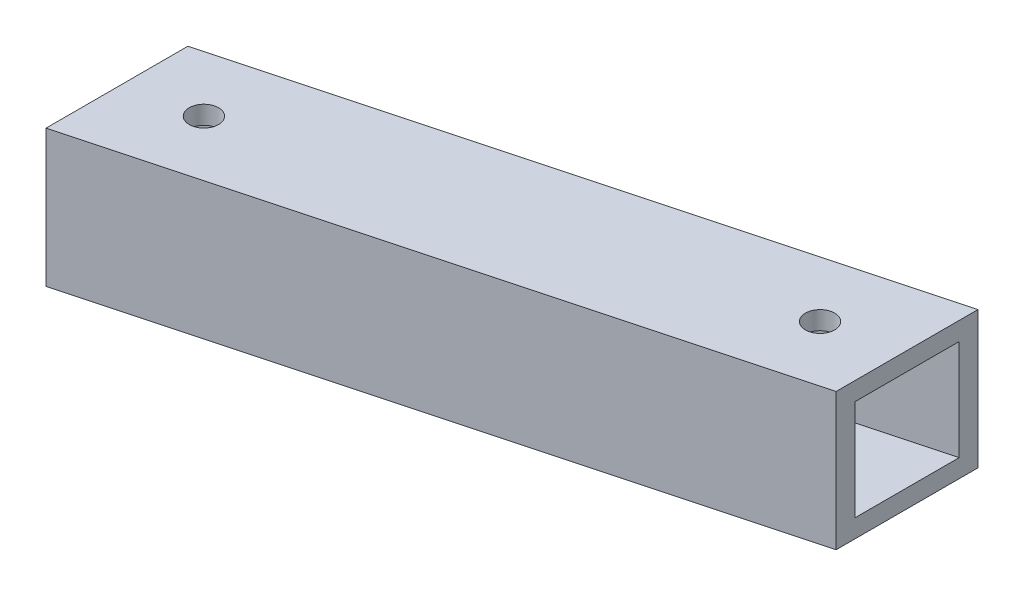
SolidWorks part; units mm, degrees
ref_plane "Front Plane" through (0, 0, 0) normal (0, 0, 1) x (1, 0, 0)
ref_plane "Top Plane" through (0, 0, 0) normal (0, 1, 0) x (1, 0, 0)
ref_plane "Right Plane" through (0, 0, 0) normal (1, 0, 0) x (0, 0, -1)
sketch "Sketch1" plane through (0, 0, 0) normal (0, 1, 0) x (1, 0, 0)
  line L0 (0, 0) -> (130, 34.8334) construction
  line L1 (0, 0) -> (130, 0) construction
  line L2 (0, 0) -> (0, 34.8334) construction
  line L3 (0, 34.8334) -> (130, 34.8334) construction
  line L4 (130, 0) -> (130, 34.8334) construction
  line L5 (130, 34.8334) -> (54.0733, 14.4889)
  line L6 (54.0733, 14.4889) -> (57.9555, 0)
  line L7 (130, 19.3043) -> (57.9555, 0)
  line L8 (130, 19.3043) -> (126.1177, 33.7931)
  line L9 (130, 34.8334) -> (130, 19.3043)
  dimension "D1" = 75
  dimension "D2" = 130
  dimension "D3" = 15
extrude "Boss-Extrude1" add sketch "Sketch1" along normal blind 15 contours L7 L8 L5 L6
sketch "Sketch2" plane through (54.0733, 0, -14.4889) normal (0.9659, 0, -0.2588) x (-0.2588, 0, -0.9659)
  line L30 (-13, 2) -> (-2, 2)
  line L31 (-2, 2) -> (-2, 13)
  line L32 (-2, 13) -> (-13, 13)
  line L33 (-13, 13) -> (-13, 2)
  line L34 (-13, 2) -> (-2, 2)
  line L35 (-2, 2) -> (-2, 13)
  line L36 (-2, 13) -> (-13, 13)
  line L37 (-13, 13) -> (-13, 2)
  dimension "D1" = 2
extrude "Cut-Extrude1" cut sketch "Sketch2" along normal through all
sketch "Sketch3" plane through (0, 15, 0) normal (0, 1, 0) x (1, 0, 0)
  line L0 (126.1177, 33.7931) -> (126.1177, 18.264)
  line L1 (130, 19.3043) -> (57.9555, 0) construction
  line L2 (126.1177, 18.264) -> (130, 19.3043)
  line L3 (130, 19.3043) -> (126.1177, 33.7931)
  line L4 (54.0733, 14.4889) -> (57.9555, 15.5291)
  line L5 (126.1177, 33.7931) -> (54.0733, 14.4889) construction
  line L6 (57.9555, 15.5291) -> (57.9555, 0)
  line L7 (57.9555, 0) -> (54.0733, 14.4889)
extrude "Cut-Extrude2" cut sketch "Sketch3" against normal through all
sketch "Sketch4" plane through (0, 0, 0) normal (0, -1, 0) x (1, 0, 0)
  line L0 (126.1177, -26.0286) -> (57.9555, -7.7646) construction
  line L1 (126.1177, -33.7931) -> (126.1177, -18.264) construction
  line L2 (57.9555, 0) -> (57.9555, -15.5291) construction
  circle A0 centre (118.6177, -24.0189) radius 1.6
  circle A1 centre (65.4555, -9.7742) radius 1.6
  dimension "D1" = 7.5
  dimension "D2" = 7.5
  dimension "D3" = 3.2
extrude "Cut-Extrude3" cut sketch "Sketch4" against normal through all
